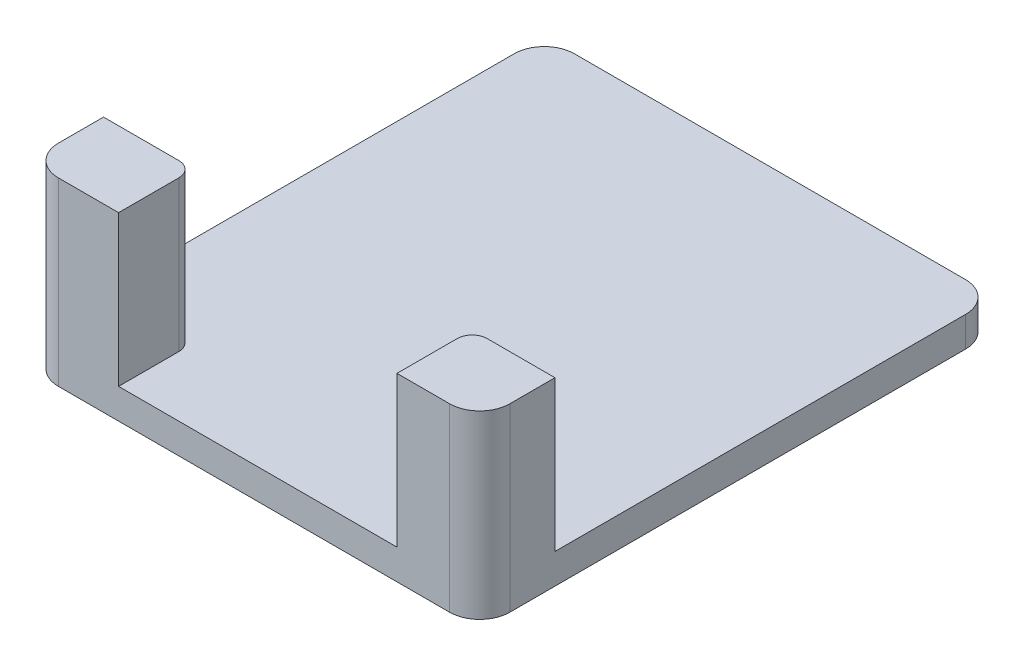
SolidWorks part; units mm, degrees
ref_plane "Front Plane" through (0, 0, 0) normal (0, 0, 1) x (1, 0, 0)
ref_plane "Top Plane" through (0, 0, 0) normal (0, 1, 0) x (1, 0, 0)
ref_plane "Right Plane" through (0, 0, 0) normal (1, 0, 0) x (0, 0, -1)
sketch "Sketch2" plane through (0, 0, 0) normal (0, 1, 0) x (1, 0, 0)
  line L1 (0, 0) -> (30, 0)
  line L2 (0, 0) -> (0, 34.29)
  line L3 (0, 34.29) -> (30, 34.29)
  line L4 (30, 0) -> (30, 34.29)
  dimension "D1" = 34.29
  dimension "D2" = 30
extrude "Boss-Extrude1" add sketch "Sketch2" along normal blind 2
sketch "Sketch3" plane through (0, 2, 0) normal (0, 1, 0) x (1, 0, 0)
  line L0 (0, 0) -> (30, 0) construction
  line L9 (24.5, 0) -> (30, 0)
  line L10 (24.5, 0) -> (24.5, 5)
  line L11 (24.5, 5) -> (30, 5)
  line L12 (30, 0) -> (30, 5)
  line L19 (30, 0) -> (30, 34.29) construction
  line L20 (0, 0) -> (6, 0)
  line L21 (0, 0) -> (0, 5)
  line L22 (0, 5) -> (6, 5)
  line L23 (6, 0) -> (6, 5)
  dimension "D1" = 5
  dimension "D2" = 5.5
  dimension "D3" = 0
  dimension "D4" = 5
  dimension "D5" = 6
extrude "Boss-Extrude2" add sketch "Sketch3" along normal blind 10
fillet "Fillet2" radius 2 4 edges at (30, 1, -34.29) (0, 1, -34.29) (30, 6, 0) (0, 6, 0)
fillet "Fillet3" radius 1 2 edges at (24.5, 7, -5) (6, 7, -5)
